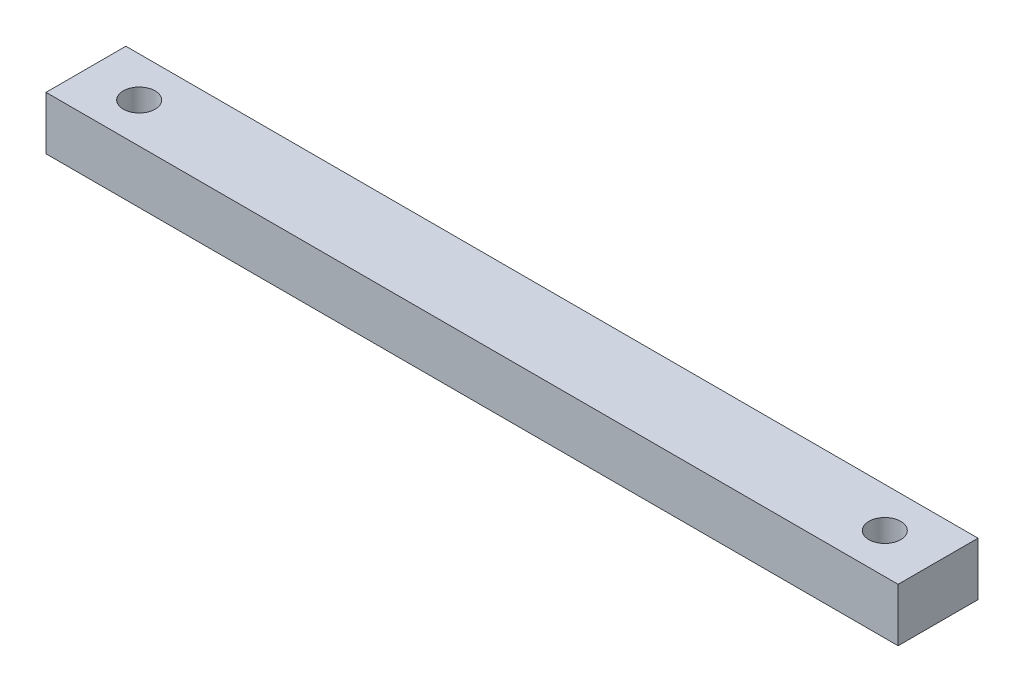
SolidWorks part; units mm, degrees
material "Custom Plastic"
ref_plane "Front Plane" through (0, 0, 0) normal (0, 0, 1) x (1, 0, 0)
ref_plane "Top Plane" through (0, 0, 0) normal (0, 1, 0) x (1, 0, 0)
ref_plane "Right Plane" through (0, 0, 0) normal (1, 0, 0) x (0, 0, -1)
sketch "Sketch1" plane through (0, 0, 0) normal (0, 1, 0) x (1, 0, 0)
  line L1 (-50.8, -4.7625) -> (50.8, -4.7625)
  line L2 (-50.8, -4.7625) -> (-50.8, 4.7625)
  line L3 (-50.8, 4.7625) -> (50.8, 4.7625)
  line L4 (50.8, -4.7625) -> (50.8, 4.7625)
  line L5 (-50.8, -4.7625) -> (50.8, 4.7625) construction
  line L6 (-50.8, 4.7625) -> (50.8, -4.7625) construction
  point P0 (0, 0)
  dimension "D1" = 101.6
  dimension "D2" = 9.525
extrude "Boss-Extrude1" add sketch "Sketch1" along normal blind 6.35
hole_wizard "#6 Clearance Hole1" positions "3DSketch1" profile "Sketch2" hole size "#6" standard "ANSI Inch" end condition through all
sketch3d "3DSketch1"
  line L0 (-50.8, 6.35, 0) -> (50.8, 6.35, 0) construction
  line L1 (-50.8, 6.35, -4.7625) -> (-50.8, 6.35, 4.7625) construction
  line L2 (50.8, 6.35, 4.7625) -> (50.8, 6.35, -4.7625) construction
  point P0 (-44.45, 6.35, 0)
  point P1 (44.45, 6.35, 0)
  point P11 (0, 0, 0)
  point P12 (0, 0, 0)
  point P13 (0, 0, 0)
  dimension "D2" = 6.35
  dimension "D1" = 6.35
sketch "Sketch2" plane through (-44.45, 6.35, 0) normal (1, 0, 0) x (0, 0, 1)
  line L0 (0, 0) -> (0, 6.35)
  line L1 (0, 6.35) -> (1.8986, 6.35)
  line L2 (1.8986, 6.35) -> (1.8986, 0)
  line L5 (1.8986, 0) -> (0, 0)
  line L11 (0, -6.35) -> (0, 107.95) construction
  dimension "Thru Hole Dia." = 3.7973
  dimension "Thru Hole Depth" = 6.35
equation "\"D2@3DSketch1\"=\"D1@3DSketch1\""
